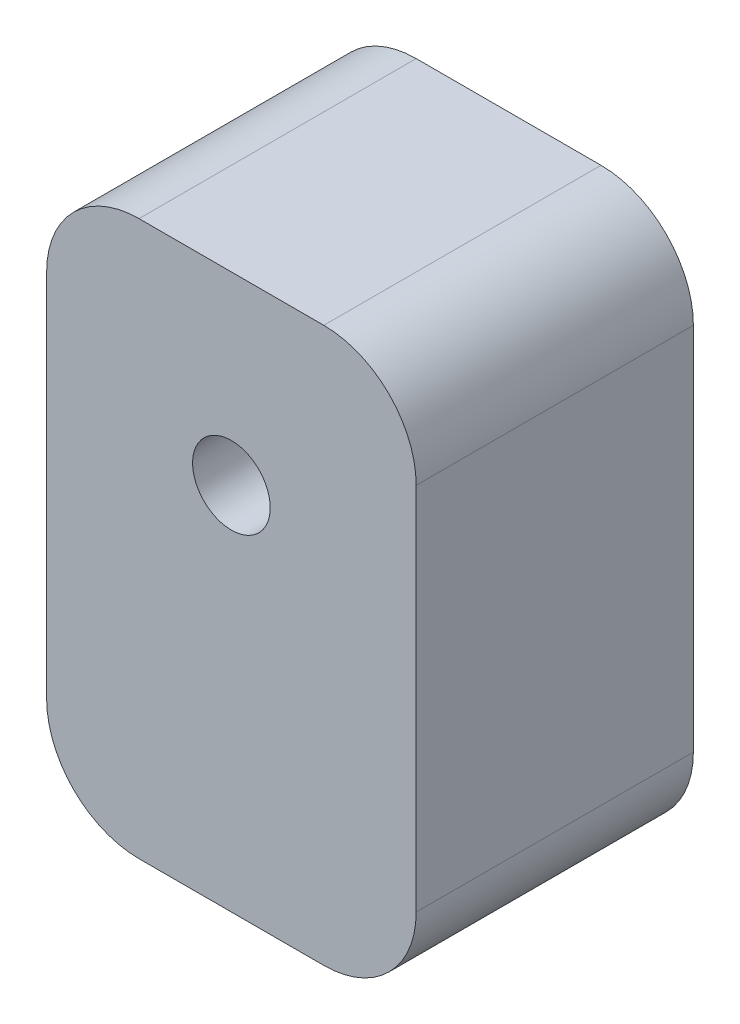
SolidWorks part; units mm, degrees
ref_plane "正面" through (0, 0, 0) normal (0, 0, 1) x (1, 0, 0)
ref_plane "平面" through (0, 0, 0) normal (0, 1, 0) x (1, 0, 0)
ref_plane "右側面" through (0, 0, 0) normal (1, 0, 0) x (0, 0, -1)
sketch "ｽｹｯﾁ2" plane through (0, 0, 0) normal (0, 0, 1) x (1, 0, 0)
  line L0 (0, 0) -> (0, 5) construction
  line L1 (-10, 15) -> (10, 15)
  line L2 (-10, 15) -> (-10, -15)
  line L3 (-10, -15) -> (10, -15)
  line L4 (10, 15) -> (10, -15)
  line L5 (-10, 15) -> (10, -15) construction
  line L6 (-10, -15) -> (10, 15) construction
  circle A0 centre (0, 5) radius 2.1
  point P0 (0, 0)
  dimension "D3" = 4.2
  dimension "D4" = 10
  dimension "D1" = 20
  dimension "D2" = 30
extrude "ﾎﾞｽ - 押し出し1" add sketch "ｽｹｯﾁ2" along normal blind 15
sketch "ｽｹｯﾁ3" plane through (0, 0, 0) normal (0, 0, -1) x (-1, 0, 0)
  line L0 (0, -10) -> (0, -15) construction
  line L1 (10, -15) -> (-10, -15) construction
  line L3 (-2.9, -5) -> (2.9, -5)
  line L4 (-2.9, -5) -> (-2.9, -15)
  line L5 (-2.9, -15) -> (2.9, -15)
  line L6 (2.9, -5) -> (2.9, -15)
  line L7 (-2.9, -5) -> (2.9, -15) construction
  line L8 (-2.9, -15) -> (2.9, -5) construction
  point P8 (2.769, -4.8147)
  dimension "D1" = 10
  dimension "D2" = 5.8
extrude "ﾎﾞｽ - 押し出し2" add sketch "ｽｹｯﾁ3" along normal blind 3
fillet "ﾌｨﾚｯﾄ1" radius 5 4 edges at (10, -15, 7.5) (-10, -15, 7.5) (-10, 15, 7.5) (10, 15, 7.5)
